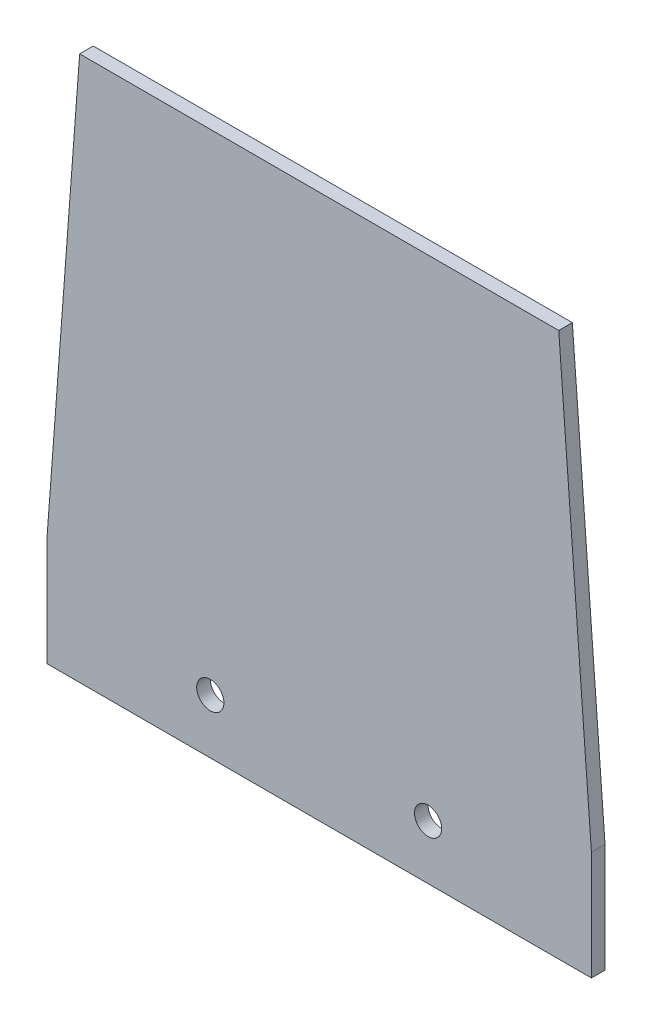
SolidWorks part; units mm, degrees
ref_plane "Front Plane" through (0, 0, 0) normal (0, 0, 1) x (1, 0, 0)
ref_plane "Top Plane" through (0, 0, 0) normal (0, 1, 0) x (1, 0, 0)
ref_plane "Right Plane" through (0, 0, 0) normal (1, 0, 0) x (0, 0, -1)
sketch "Sketch1" plane through (0, 0, 0) normal (0, 0, 1) x (1, 0, 0)
  line L0 (-63.5, -76.2) -> (63.5, -76.2)
  line L1 (-101.6, 101.6) -> (101.6, 101.6) construction
  line L2 (-101.6, 101.6) -> (-101.6, -101.6) construction
  line L3 (-101.6, -101.6) -> (101.6, -101.6) construction
  line L4 (101.6, 101.6) -> (101.6, -101.6) construction
  line L5 (-101.6, 101.6) -> (101.6, -101.6) construction
  line L6 (-101.6, -101.6) -> (101.6, 101.6) construction
  line L7 (63.5, -76.2) -> (63.5, -101.6)
  line L8 (63.5, -101.6) -> (-63.5, -101.6)
  line L9 (-63.5, -101.6) -> (-63.5, -76.2)
  line L10 (-63.5, -76.2) -> (-55.88, 25.4)
  line L11 (-55.88, 25.4) -> (55.88, 25.4)
  line L12 (55.88, 25.4) -> (63.5, -76.2)
  point P0 (0, 0)
  dimension "D1" = 203.2
  dimension "D2" = 203.2
extrude "Boss-Extrude1" add sketch "Sketch1" along normal blind 3.175 contours L12 L11 L10 L0 | L9 L8 L7 L0
sketch "Sketch2" plane through (0, 0, 3.175) normal (0, 0, 1) x (1, 0, 0)
  line L0 (-101.6, -101.6) -> (101.6, -101.6) construction
  line L1 (-101.6, 101.6) -> (-101.6, -101.6) construction
  line L2 (101.6, -101.6) -> (101.6, 101.6) construction
  circle A0 centre (-25.4, -88.9) radius 3.175
  circle A1 centre (25.4, -88.9) radius 3.175
  dimension "D1" = 12.7
  dimension "D2" = 12.7
  dimension "D3" = 6.35
  dimension "D4" = 76.2
  dimension "D5" = 76.2
extrude "Cut-Extrude1" cut sketch "Sketch2" against normal blind 3.175
